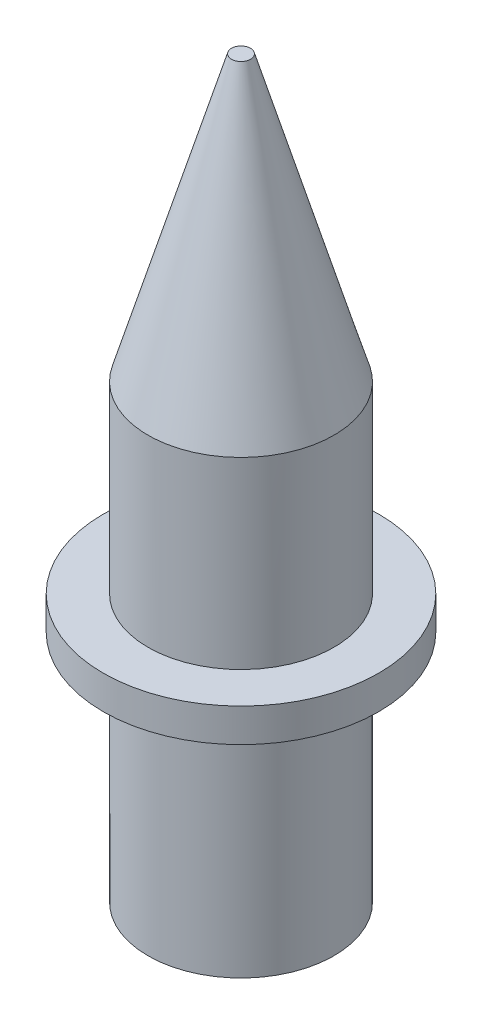
SolidWorks part; units mm, degrees
ref_plane "Front Plane" through (0, 0, 0) normal (0, 0, 1) x (1, 0, 0)
ref_plane "Top Plane" through (0, 0, 0) normal (0, 1, 0) x (1, 0, 0)
ref_plane "Right Plane" through (0, 0, 0) normal (1, 0, 0) x (0, 0, -1)
sketch "Sketch1" plane through (0, 0, 0) normal (0, 1, 0) x (1, 0, 0)
  circle A0 centre (0, 0) radius 5.57
  dimension "D1" = 11.14
extrude "Boss-Extrude1" add sketch "Sketch1" along normal blind 44
chamfer "Chamfer1" distance 17 distance2 5 1 edges at (0, 44, 5.57)
ref_plane "Plane1" through (0, 16, 0) normal (0, 1, 0) x (1, 0, 0)
sketch "Sketch2" plane through (0, 16, 0) normal (0, 1, 0) x (1, 0, 0)
  circle A0 centre (0, 0) radius 8.25
  dimension "D1" = 16.5
extrude "Boss-Extrude2" add sketch "Sketch2" against normal blind 2
